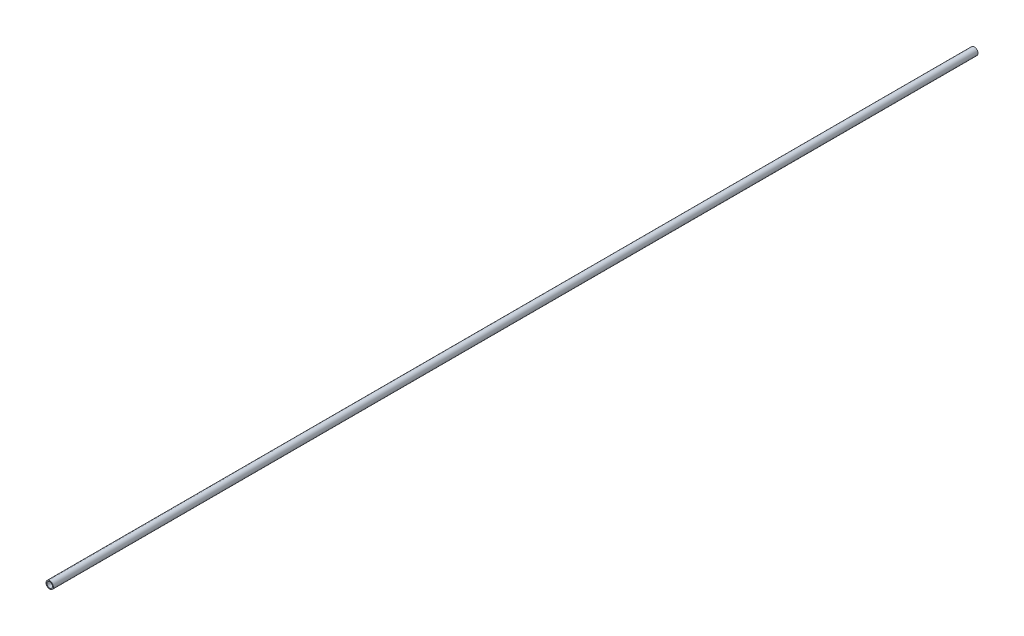
SolidWorks part; units mm, degrees
ref_plane "Front Plane" through (0, 0, 0) normal (0, 0, 1) x (1, 0, 0)
ref_plane "Top Plane" through (0, 0, 0) normal (0, 1, 0) x (1, 0, 0)
ref_plane "Right Plane" through (0, 0, 0) normal (1, 0, 0) x (0, 0, -1)
sketch "Sketch2" plane through (0, 0, 0) normal (0, 0, 1) x (1, 0, 0)
  circle A0 centre (0, 0) radius 4
  circle A1 centre (0, 0) radius 3
  dimension "D1" = 8
  dimension "D2" = 6
extrude "Boss-Extrude1" add sketch "Sketch2" along normal blind 1000
